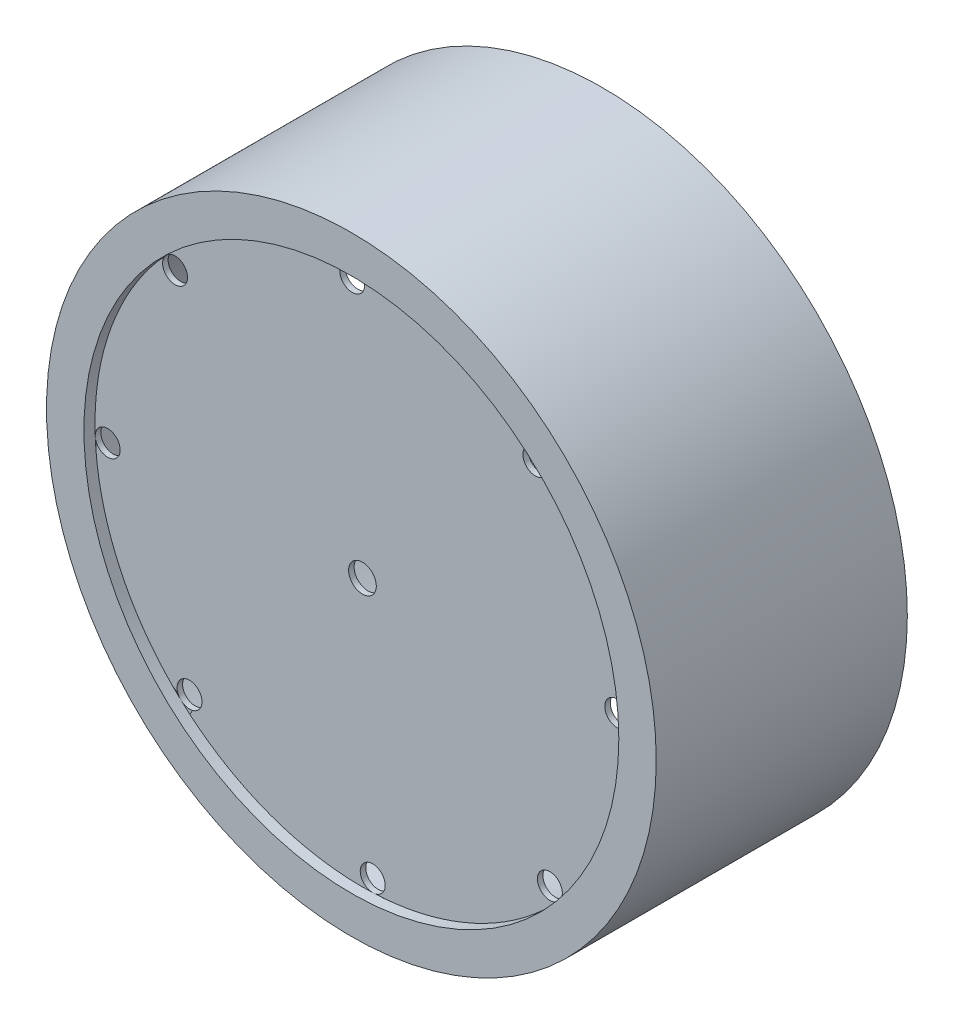
SolidWorks part; units mm, degrees
ref_plane "前视基准面" through (0, 0, 0) normal (0, 0, 1) x (1, 0, 0)
ref_plane "上视基准面" through (0, 0, 0) normal (0, 1, 0) x (1, 0, 0)
ref_plane "右视基准面" through (0, 0, 0) normal (1, 0, 0) x (0, 0, -1)
sketch "草图1" plane through (0, 0, 0) normal (0, 0, 1) x (1, 0, 0)
  circle A0 centre (0, 0) radius 55
extrude "凸台-拉伸3" add sketch "草图1" along normal blind 45.3
sketch "草图5" plane through (0, 0, 0) normal (0, 0, -1) x (-1, 0, 0)
  circle A0 centre (0, 0) radius 50
extrude "切除-拉伸3" cut sketch "草图5" against normal blind 42.3
sketch "草图6" plane through (0, 0, 42.3) normal (0, 0, -1) x (-1, 0, 0)
  circle A1 centre (31.1942, -33.8071) radius 2.25
  circle A2 centre (-1.8476, -45.9629) radius 2.25
  circle A3 centre (-33.8071, -31.1942) radius 2.25
  circle A4 centre (-45.9629, 1.8476) radius 2.25
  circle A5 centre (-31.1942, 33.8071) radius 2.25
  circle A6 centre (1.8476, 45.9629) radius 2.25
  circle A7 centre (33.8071, 31.1942) radius 2.25
  circle A8 centre (45.9629, -1.8476) radius 2.25
  point P22 (0, 0)
  dimension "D1" = 8
sketch "草图8" plane through (0, 0, 45.3) normal (0, 0, 1) x (1, 0, 0)
  circle A0 centre (0, 0) radius 48.25
extrude "切除-拉伸4" cut sketch "草图8" against normal blind 2
extrude "切除-拉伸6" cut sketch "草图6" against normal blind 2 contours A2 | A3 | A4 | A5 | A1 | A6 | A7 | A8
sketch "草图9" plane through (0, 0, 0) normal (0, 0, -1) x (-1, 0, 0)
  line L0 (0, 0) -> (55, 0)
  circle A0 centre (0, 0) radius 55 construction
sketch "草图10" plane through (0, 0, 42.3) normal (0, 0, -1) x (-1, 0, 0)
  circle A0 centre (0, 0) radius 2.5
extrude "切除-拉伸7" cut sketch "草图10" against normal blind 5
sketch "草图12" plane through (0, 0, 0) normal (0, 0, -1) x (-1, 0, 0)
  line L0 (55, 0) -> (55, -2.5)
  line L1 (54.8457, -2.5) -> (84.8457, -2.5)
  line L2 (84.8457, -2.5) -> (84.8457, -3.5)
  line L3 (84.8457, -3.5) -> (54.7834, -3.5)
  line L4 (54.7834, -3.5) -> (54.8457, -2.5)
sketch "草图17" plane through (0, 0, 45.3) normal (0, 0, 1) x (1, 0, 0)
  line L0 (-52.915, -15) -> (-82.915, -15)
  line L1 (-60, -15) -> (-120, -15) construction
  line L2 (-82.915, -15) -> (-82.915, -13.9991)
  circle A0 centre (0, 0) radius 55 construction
sketch "草图18" plane through (0, 0, 0) normal (0, 0, -1) x (-1, 0, 0)
  line L0 (52.8329, -15) -> (82.8329, -15)
  line L1 (120, -15) -> (50, -15) construction
  line L2 (52.915, -15) -> (82.915, -15) construction
  line L3 (82.8329, -15) -> (82.8329, -13.9978)
  line L4 (82.8329, -13.9978) -> (53.1519, -13.9978)
  line L5 (53.1519, -13.9978) -> (52.8346, -15)
  circle M5 centre (0, 0) radius 55
extrude "凸台-拉伸9" add sketch "草图18" against normal blind 15 contours L3 L4 L0 M5
sketch "草图19" plane through (0, 0, 0) normal (0, 0, -1) x (-1, 0, 0)
  line L0 (51.2348, -20) -> (82.8329, -20)
  line L1 (120, -20) -> (50, -20) construction
  line L2 (205, -20) -> (75.5521, -20) construction
  line L3 (82.8329, -20) -> (82.8329, -20.9994)
  line L4 (82.8329, -20.9994) -> (50.7653, -20.9994)
  line L5 (50.7653, -20.9994) -> (51.2253, -20)
  line L6 (51.2253, -20) -> (51.2348, -20)
  arc A0 (53.1889, -13.9978) -> (52.915, -15) centre (0, 0) ccw construction
extrude "凸台-拉伸10" add sketch "草图19" against normal blind 15
sketch "草图20" plane through (0, -20.9994, 0) normal (0, -1, 0) x (-1, 0, 0)
  line L0 (82.8329, -7.5) -> (75.3329, -7.5)
  line L1 (82.8329, -15) -> (82.8329, 0) construction
  circle A0 centre (75.3329, -7.5) radius 2.5
extrude "切除-拉伸9" cut sketch "草图20" against normal blind 8
